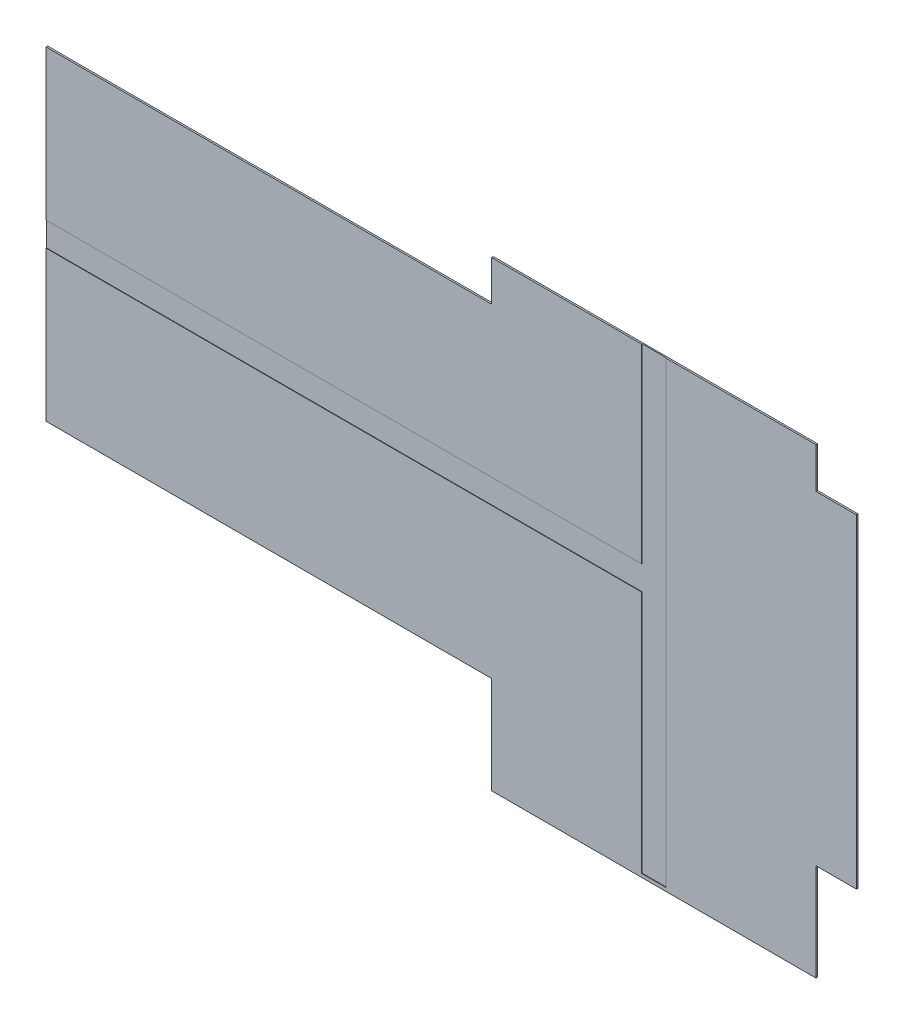
SolidWorks part; units mm, degrees
ref_plane "Front Plane" through (0, 0, 0) normal (0, 0, 1) x (1, 0, 0)
ref_plane "Top Plane" through (0, 0, 0) normal (0, 1, 0) x (1, 0, 0)
ref_plane "Right Plane" through (0, 0, 0) normal (1, 0, 0) x (0, 0, -1)
sketch "Sketch1" plane through (0, 0, 0) normal (0, 0, 1) x (1, 0, 0)
  line L1 (-568.9023, 252.7985) -> (431.0977, 252.7985)
  line L2 (-568.9023, 252.7985) -> (-568.9023, -317.2015)
  line L3 (-568.9023, -317.2015) -> (431.0977, -317.2015)
  line L4 (431.0977, 252.7985) -> (431.0977, -317.2015)
  line L13 (381.0977, 252.7985) -> (431.0977, 252.7985)
  line L14 (381.0977, 252.7985) -> (381.0977, 202.7985)
  line L15 (381.0977, 202.7985) -> (431.0977, 202.7985)
  line L16 (431.0977, 252.7985) -> (431.0977, 202.7985)
  line L17 (-568.9023, 252.7985) -> (-18.9023, 252.7985)
  line L18 (-568.9023, 252.7985) -> (-568.9023, 202.7985)
  line L19 (-568.9023, 202.7985) -> (-18.9023, 202.7985)
  line L20 (-18.9023, 252.7985) -> (-18.9023, 202.7985)
  line L21 (-568.9023, -317.2015) -> (-18.9023, -317.2015)
  line L22 (-568.9023, -317.2015) -> (-568.9023, -197.2015)
  line L23 (-568.9023, -197.2015) -> (-18.9023, -197.2015)
  line L24 (-18.9023, -317.2015) -> (-18.9023, -197.2015)
  line L25 (381.0977, -197.2015) -> (431.0977, -197.2015)
  line L26 (381.0977, -197.2015) -> (381.0977, -317.2015)
  line L27 (381.0977, -317.2015) -> (431.0977, -317.2015)
  line L28 (431.0977, -197.2015) -> (431.0977, -317.2015)
  dimension "D1" = 1000
  dimension "D2" = 570
  dimension "D3" = 0
  dimension "D4" = 50
  dimension "D5" = 50
  dimension "D6" = 0
  dimension "D7" = 0
  dimension "D8" = 0
  dimension "D9" = 50
  dimension "D10" = 550
  dimension "D11" = 550
  dimension "D12" = 120
  dimension "D13" = 0
  dimension "D14" = 0
  dimension "D15" = 0
  dimension "D16" = 0
  dimension "D17" = 120
  dimension "D18" = 50
extrude "Boss-Extrude2" add sketch "Sketch1" along normal blind 2 contours L26 L25 L4 L15 L14 L1 L20 L19 L2 L23 L24 L3
sketch "Sketch3" plane through (0, 0, 2) normal (0, 0, 1) x (1, 0, 0)
  line L0 (-568.9023, 202.7985) -> (-18.9023, 202.7985) construction
  line L1 (-569.9959, 17.7985) -> (166.0977, 17.7985)
  line L2 (-569.9959, 17.7985) -> (-569.9959, -12.2015)
  line L3 (-569.9959, -12.2015) -> (166.0977, -12.2015)
  line L4 (166.0977, 17.7985) -> (166.0977, -12.2015)
  line L5 (-568.9023, -197.2015) -> (-18.9023, -197.2015) construction
  line L6 (-18.9023, 252.7985) -> (-18.9023, 202.7985) construction
  line L7 (166.0977, 253.9068) -> (196.0977, 253.9068)
  line L8 (166.0977, 253.9068) -> (166.0977, -312.9217)
  line L9 (166.0977, -312.9217) -> (196.0977, -312.9217)
  line L10 (196.0977, 253.9068) -> (196.0977, -312.9217)
  line L11 (381.0977, 252.7985) -> (381.0977, 202.7985) construction
  line M14 (-568.9023, 202.7985) -> (-568.9023, -197.2015)
  dimension "D1" = 185
  dimension "D2" = 185
  dimension "D3" = 185
  dimension "D4" = 185
  dimension "D5" = 0
extrude "Cut-Extrude1" cut sketch "Sketch3" against normal blind 0.5 contours L4 L1 L3 M14 | L10 L9 L8 L7
